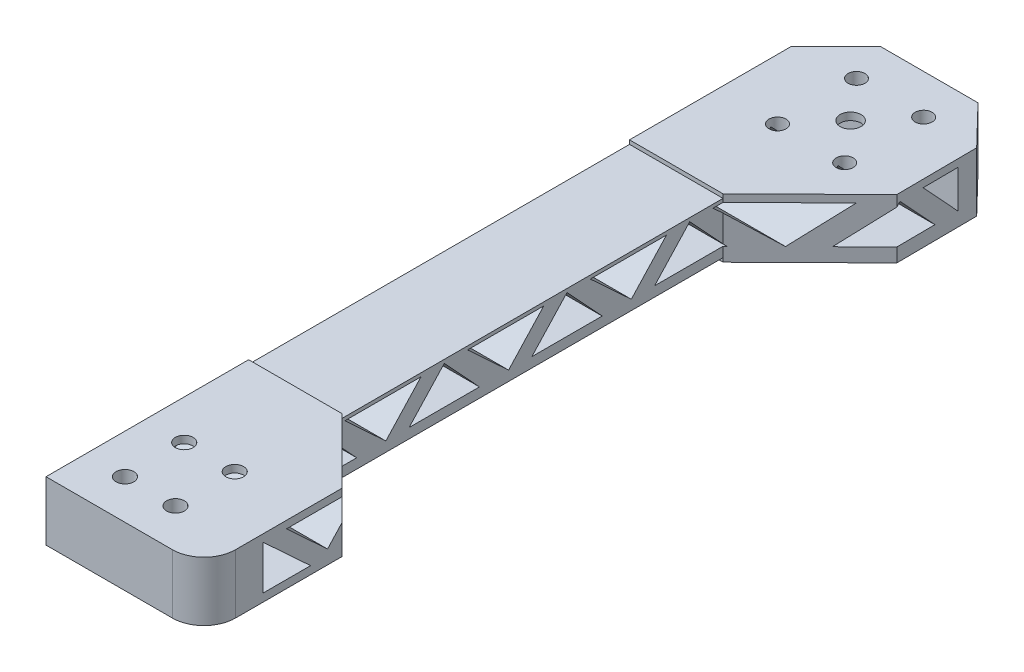
SolidWorks part; units mm, degrees
material "Steel alloy"
ref_plane "Front Plane" through (0, 0, 0) normal (0, 0, 1) x (1, 0, 0)
ref_plane "Top Plane" through (0, 0, 0) normal (0, 1, 0) x (1, 0, 0)
ref_plane "Right Plane" through (0, 0, 0) normal (1, 0, 0) x (0, 0, -1)
sketch "Sketch1" plane through (0, 0, 0) normal (0, 1, 0) x (1, 0, 0)
  line L0 (-15.2646, -1.2533) -> (-15.2646, -189.9714)
  line L1 (-15.2646, -189.9714) -> (16.7354, -189.9714)
  line L2 (24.7354, -181.9714) -> (24.7354, -154.9714)
  line L3 (24.7354, -154.9714) -> (8.421, -138.657)
  line L4 (8.421, -138.657) -> (8.421, -42.2118)
  line L10 (30.584, -20.3769) -> (8.421, -42.2118)
  line L11 (-15.2646, -1.2533) -> (-3.9828, 10.0286)
  line L12 (-3.9828, 10.0286) -> (20.7366, 10.0286)
  line L13 (30.4294, 0) -> (30.584, -20.3769)
  line L14 (20.7366, 10.0286) -> (30.4294, 0)
  arc A0 (16.7354, -189.9714) -> (24.7354, -181.9714) centre (16.7354, -181.9714) ccw
  circle A1 centre (-5.2646, -179.9714) radius 2.25
  circle A2 centre (7.5256, -179.9714) radius 2.25
  circle A3 centre (-5.2646, -164.9714) radius 2.25
  circle A4 centre (7.5256, -164.9714) radius 2.25
  circle A9 centre (8.5, -10) radius 2.65
  circle A10 centre (0, 0) radius 2.15
  circle A11 centre (17, 0) radius 2.15
  circle A12 centre (0, -20) radius 2.15
  circle A13 centre (17, -20) radius 2.15
  point P8 (24.7354, -189.9714)
  dimension "D4" = 8
  dimension "D12" = 4.5
  dimension "D13" = 4.5
  dimension "D14" = 4.5
  dimension "D15" = 4.5
  dimension "D17" = 10
  dimension "D18" = 4.3
  dimension "D19" = 4.3
  dimension "D20" = 4.3
  dimension "D21" = 4.3
  dimension "D22" = 5.3
  dimension "D2" = 40
  dimension "D3" = 35
  dimension "D5" = 20
  dimension "D6" = 10
  dimension "D7" = 10
  dimension "D8" = 10
  dimension "D9" = 10
  dimension "D10" = 15
  dimension "D11" = 15
  dimension "D16" = 8.5
  dimension "D23" = 8.5
  dimension "D24" = 8.5
  dimension "D25" = 10
  dimension "D26" = 10
  dimension "D27" = 200
extrude "Boss-Extrude1" add sketch "Sketch1" along normal blind 15
sketch "Sketch2" plane through (-15.2646, 0, 0) normal (-1, 0, 0) x (0, 0, 1)
  line L0 (-10.0286, 7.5) -> (189.9714, 7.5) construction
  line L1 (-10.0286, 15) -> (-10.0286, 0) construction
  line L2 (189.9714, 15) -> (189.9714, 0) construction
  line L3 (-10.0286, 11.5) -> (189.9714, 11.5) construction
  line L4 (-10.0286, 3.5) -> (189.9714, 3.5) construction
  line L5 (-10.0286, 2) -> (189.9714, 2) construction
  line L6 (189.9714, 13.114) -> (-10.0286, 13.114) construction
  line L9 (174.9714, 13.114) -> (174.9714, 2)
  line L10 (174.9714, 2) -> (162.9714, 2)
  line L11 (162.9714, 2) -> (174.9714, 13.114)
  line L13 (149.782, 13.114) -> (169.0666, 13.114)
  line L14 (169.0666, 13.114) -> (158.6861, 3.5)
  line L15 (158.6861, 3.5) -> (149.782, 13.114)
  line L18 (4.7579, 3.5) -> (4.7579, 13.114)
  line L19 (143.882, 13.114) -> (152.7861, 3.5)
  line L20 (152.7861, 3.5) -> (143.882, 3.5)
  line L21 (112.802, 13.114) -> (121.7061, 3.5)
  line L22 (143.882, 3.5) -> (134.9779, 3.5)
  line L23 (143.882, 13.114) -> (134.9779, 3.5)
  line L24 (121.7061, 3.5) -> (112.802, 3.5)
  line L25 (112.802, 3.5) -> (103.8979, 3.5)
  line L26 (112.802, 13.114) -> (103.8979, 3.5)
  line L27 (81.722, 13.114) -> (90.6261, 3.5)
  line L28 (90.6261, 3.5) -> (81.722, 3.5)
  line L29 (81.722, 3.5) -> (72.8179, 3.5)
  line L30 (81.722, 13.114) -> (72.8179, 3.5)
  line L31 (50.642, 13.114) -> (59.5461, 3.5)
  line L32 (59.5461, 3.5) -> (50.642, 3.5)
  line L33 (50.642, 3.5) -> (41.7379, 3.5)
  line L34 (50.642, 13.114) -> (41.7379, 3.5)
  line L35 (19.562, 13.114) -> (28.4661, 3.5)
  line L36 (28.4661, 3.5) -> (19.562, 3.5)
  line L37 (19.562, 3.5) -> (10.6579, 3.5)
  line L38 (19.562, 13.114) -> (10.6579, 3.5)
  line L39 (137.9866, 13.114) -> (127.6061, 3.5)
  line L40 (118.702, 13.114) -> (137.9866, 13.114)
  line L41 (127.6061, 3.5) -> (118.702, 13.114)
  line L42 (106.9066, 13.114) -> (96.5261, 3.5)
  line L43 (87.622, 13.114) -> (106.9066, 13.114)
  line L44 (96.5261, 3.5) -> (87.622, 13.114)
  line L45 (75.8266, 13.114) -> (65.4461, 3.5)
  line L46 (56.542, 13.114) -> (75.8266, 13.114)
  line L47 (65.4461, 3.5) -> (56.542, 13.114)
  line L48 (44.7466, 13.114) -> (34.3661, 3.5)
  line L49 (25.462, 13.114) -> (44.7466, 13.114)
  line L50 (34.3661, 3.5) -> (25.462, 13.114)
  line L51 (4.7579, 13.114) -> (13.662, 13.114)
  line L52 (13.662, 13.114) -> (4.7579, 3.5)
  dimension "D1" = 15
  dimension "D2" = 12
  dimension "D3" = 5.9
  dimension "D4" = 5.9
  dimension "D5" = 8.9041
  dimension "D6" = 8.9041
  dimension "D7" = 5
  dimension "D8" = 5
  dimension "D9" = 5.9
  dimension "D10" = 5.9
extrude "Cut-Extrude2" cut sketch "Sketch2" against normal blind 46
sketch "Sketch3" plane through (0, 0, 0) normal (0, -1, 0) x (1, 0, 0)
  line L0 (8.421, 42.2118) -> (-15.2646, 42.2118)
  line L1 (-15.2646, 1.2533) -> (-15.2646, 189.9714) construction
  line L3 (8.421, 138.657) -> (-15.2646, 138.657)
  line L4 (-15.2646, 138.657) -> (-15.2646, 42.2118)
  line L5 (8.421, 138.657) -> (8.421, 42.2118)
extrude "Cut-Extrude4" cut sketch "Sketch3" against normal blind 1
sketch "Sketch4" plane through (0, 15, 0) normal (0, 1, 0) x (1, 0, 0)
  line L0 (8.421, -42.2118) -> (-15.2646, -42.2118)
  line L2 (8.421, -138.657) -> (-15.2646, -138.657)
  line L3 (-15.2646, -1.2533) -> (-15.2646, -189.9714) construction
  line L4 (-15.2646, -138.657) -> (-15.2646, -42.2118)
  line L5 (8.421, -42.2118) -> (8.421, -138.657)
extrude "Cut-Extrude5" cut sketch "Sketch4" against normal blind 1
